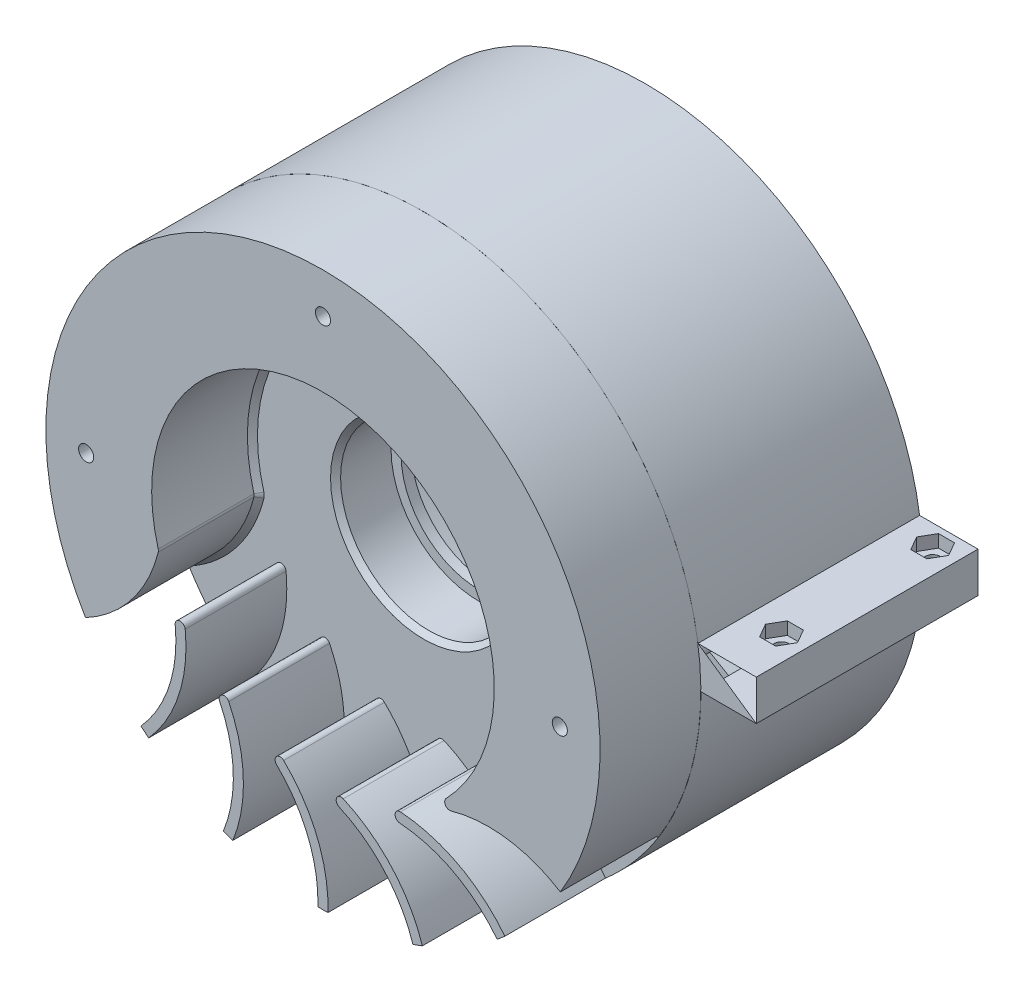
SolidWorks part; units mm, degrees
material "ABS"
ref_plane "前视基准面" through (0, 0, 0) normal (0, 0, 1) x (1, 0, 0)
ref_plane "上视基准面" through (0, 0, 0) normal (0, 1, 0) x (1, 0, 0)
ref_plane "右视基准面" through (0, 0, 0) normal (1, 0, 0) x (0, 0, -1)
other "Configuration Table"
sketch "草图1" plane through (0, 0, 0) normal (1, 0, 0) x (0, 0, -1)
  line L0 (0, 0) -> (32.5576, 0) construction
  line L1 (0, 17.5) -> (44, 17.5)
  line L2 (0, 17.5) -> (0, 55)
  line L3 (0, 55) -> (44, 55)
  line L4 (44, 17.5) -> (44, 55)
  dimension "D1" = 17.5
  dimension "D2" = 55
  dimension "D3" = 44
sketch "草图2" plane through (0, 0, 0) normal (0, 0, 1) x (1, 0, 0)
  line L0 (-33.6531, -9.6161) -> (-22.355, -49.1554) construction
  line L3 (-52.8896, -16.3925) -> (-45.4407, -29.2943) construction
  line L4 (-45.7638, -26.4218) -> (-39.6155, -22.872) construction
  line L5 (0, 0) -> (0, -27.9556) construction
  line L6 (-33.6531, -9.6161) -> (-40.2555, -35.993) construction
  circle A0 centre (0, 0) radius 35 construction
  circle A1 centre (0, 0) radius 54 construction
  arc A4 (-33.6531, -9.6161) -> (-46.7654, -27) centre (-60.7125, -2.8429) cw construction
  arc A5 (-46.2654, -27.866) -> (-32.683, -9.859) centre (-60.7125, -2.8429) ccw
  arc A6 (-47.2654, -26.134) -> (-34.6231, -9.3733) centre (-60.7125, -2.8429) ccw
  arc A7 (-47.2654, -26.134) -> (-46.2654, -27.866) centre (-46.7654, -27) ccw construction
  arc A8 (-32.683, -9.859) -> (-34.6231, -9.3733) centre (-33.6531, -9.6161) ccw
  arc A9 (-47.2654, -26.134) -> (-48.1283, -26.6113) centre (-60.7125, -2.8429) cw
  arc A10 (-54.7677, -5.0001) -> (54.7677, -5.0001) centre (0, 0) ccw construction
  arc A11 (-46.2654, -27.866) -> (-47.1283, -28.3448) centre (-60.7125, -2.8429) cw
  arc A12 (-47.1283, -28.3448) -> (-48.1283, -26.6113) centre (0, 0) cw
  point P6 (-38.4429, -19.6404)
  dimension "D1" = 70
  dimension "D2" = 108
  dimension "D3" = 1
  dimension "D4" = 60
  dimension "D5" = 30
extrude "凸台-拉伸1" add sketch "草图2" along normal blind 20 contours A12 A11 A5 A8 A6 A9
revolve "旋转1" add sketch "草图1" angle 360 about L0
pattern_circular "阵列(圆周)1" count 7 every 20 about axis through (0, 0, 0) along (0, 0, 1) of "凸台-拉伸1"
sketch "草图3" plane through (0, 0, 0) normal (0, 0, 1) x (1, 0, 0)
  arc A9 (-47.1283, -28.3448) -> (47.1103, -28.3747) centre (0, 0) cw
  arc A20 (-32.6916, -9.3414) -> (24.4357, -23.641) centre (0, 0) cw
  arc A22 (24.8796, -23.3748) -> (25.4291, -25.2979) centre (25.1544, -24.3363) ccw construction
  arc A23 (-47.1283, -28.3448) -> (-32.683, -9.859) centre (-60.7125, -2.8429) ccw construction
  arc A24 (-47.1283, -28.3448) -> (-32.683, -9.859) centre (-60.7125, -2.8429) ccw
  arc A25 (47.1103, -28.3747) -> (25.4291, -25.2979) centre (32.8182, -51.1571) ccw
  arc A26 (-32.683, -9.859) -> (-32.6916, -9.3414) centre (-33.6531, -9.6161) ccw
  arc A27 (24.4357, -23.641) -> (25.4291, -25.2979) centre (25.1544, -24.3363) ccw
  arc A28 (47.1103, -28.3747) -> (25.4291, -25.2979) centre (32.8182, -51.1571) ccw construction
extrude "凸台-拉伸2" add sketch "草图3" along normal up to surface (20 mm away) up to face at (-39.6333, -19.0479, 20)
sketch "草图4" plane through (0, 0, -44) normal (0, 0, -1) x (-1, 0, 0)
  line L0 (-50, 0) -> (-47, 0) construction
  line L1 (-45.25, 3.0311) -> (-49.6863, 5.5924)
  line L2 (-45.25, -3.0311) -> (-49.6863, -5.5924)
  line L3 (3.0311, 45.25) -> (5.5924, 49.6863)
  line L4 (-3.0311, 45.25) -> (-5.5924, 49.6863)
  line L5 (0, 50) -> (0, 47) construction
  line L6 (45.25, -3.0311) -> (49.6863, -5.5924)
  line L7 (45.25, 3.0311) -> (49.6863, 5.5924)
  line L8 (50, 0) -> (47, 0) construction
  line L9 (-3.0311, -45.25) -> (-5.5924, -49.6863)
  line L10 (3.0311, -45.25) -> (5.5924, -49.6863)
  line L11 (0, -50) -> (0, -47) construction
  line L12 (-49.9706, -1.7151) -> (-49.9706, 1.7151) construction
  line L13 (-49.9706, 1.7151) -> (-47, 0) construction
  circle A0 centre (0, 0) radius 50 construction
  circle A1 centre (0, 0) radius 55 construction
  arc A2 (-45.25, -3.0311) -> (-45.25, 3.0311) centre (-47, 0) ccw
  circle A3 centre (-47, 0) radius 1.5
  arc A4 (-49.6863, 5.5924) -> (-35.3553, 35.3553) centre (0, 0) cw
  arc A5 (-49.6863, -5.5924) -> (-31.1791, -39.0879) centre (0, 0) ccw
  arc A6 (-3.0311, 45.25) -> (3.0311, 45.25) centre (0, 47) ccw
  circle A7 centre (0, 47) radius 1.5
  arc A8 (5.5924, 49.6863) -> (35.3553, 35.3553) centre (0, 0) cw
  arc A9 (-5.5924, 49.6863) -> (-39.0879, 31.1791) centre (0, 0) ccw
  arc A10 (45.25, 3.0311) -> (45.25, -3.0311) centre (47, 0) ccw
  circle A11 centre (47, 0) radius 1.5
  arc A12 (49.6863, -5.5924) -> (35.3553, -35.3553) centre (0, 0) cw
  arc A13 (49.6863, 5.5924) -> (31.1791, 39.0879) centre (0, 0) ccw
  arc A14 (3.0311, -45.25) -> (-3.0311, -45.25) centre (0, -47) ccw
  circle A15 centre (0, -47) radius 1.5
  arc A16 (-5.5924, -49.6863) -> (-35.3553, -35.3553) centre (0, 0) cw
  arc A17 (5.5924, -49.6863) -> (39.0879, -31.1791) centre (0, 0) ccw
  point P44 (0, 0)
  circle M8 centre (0, 0) radius 17.5
  dimension "D1" = 5
  dimension "D2" = 3
  dimension "D3" = 2
  dimension "D6" = 45
  dimension "D4" = 30
  dimension "D5" = 30
  dimension "D7" = 45
  dimension "D10" = 60
  dimension "D11" = 47
  dimension "D8" = 4
extrude "切除-拉伸1" cut sketch "草图4" against normal offset from surface (33 mm away) 11 contours L10 A17 A12 L6 A10 L7 A13 A8 L3 A6 L4 A9 A4 L1 A2 L2 A5 A16 L9 A14 M8 | A7 | A11 | A15 | A3 up to face at (25.6408, -35.7236, 0)
sketch "草图5" plane through (0, 0, -11) normal (0, 0, -1) x (-1, 0, 0)
  circle A0 centre (-47, 0) radius 1.5 construction
  circle A1 centre (0, 47) radius 1.5
  circle A2 centre (0, 47) radius 1.5
  circle A3 centre (-47, 0) radius 1.5
  circle A6 centre (47, 0) radius 1.5 construction
  circle A7 centre (47, 0) radius 1.5
  dimension "D1" = 0
extrude "切除-拉伸2" cut sketch "草图5" against normal up to surface (31 mm away) up to face at (-0.2385, 1.394, 20)
sketch "草图7" plane through (0, 0, -11) normal (0, 0, -1) x (-1, 0, 0)
  circle A10 centre (0, 0) radius 19.5
  circle A11 centre (0, 0) radius 19.5
  circle A12 centre (0, 0) radius 15.5
  circle A13 centre (0, 0) radius 15.5
  dimension "D1" = 2
  dimension "D2" = 2
extrude "凸台-拉伸3" add sketch "草图7" along normal blind 2
chamfer "倒角2" distance 1 angle 45 1 edges at (17.5, 0, 0)
chamfer "倒角3" distance 1 angle 45 5 edges at (24.2967, -24.8506, 0) (8.2559, 32.9824, 0) (-32.6532, -9.5996, 0) (-37.9451, -20.6339, 0) (36.597, -24.5297, 0)
sketch "草图9" plane through (0, 0, 0) normal (0, 1, 0) x (1, 0, 0)
  line L0 (-55, 44) -> (-55, 0) construction
  line L11 (-55, 44) -> (-55, 0)
  line L12 (-55, 44) -> (-66, 44)
  line L13 (-66, 44) -> (-66, 0)
  line L14 (-66, 0) -> (-55, 0)
  line L15 (0, -55) -> (0, 55) construction
  line L16 (66, 44) -> (66, 0)
  line L17 (55, 44) -> (66, 44)
  line L18 (55, 44) -> (55, 0)
  line L19 (66, 0) -> (55, 0)
  dimension "D1" = 11
extrude "凸台-拉伸4" add sketch "草图9" along normal blind 8
sketch "草图12" plane through (-55, 0, 0) normal (1, 0, 0) x (0, 0, -1)
  line L4 (0, 0) -> (44, 0)
  line L5 (44, 0) -> (44, 8)
  line L6 (44, 8) -> (0, 8)
  line L7 (0, 8) -> (0, 0)
  line L8 (0, 0) -> (44, 0)
  line L9 (44, 0) -> (44, 8)
  line L10 (44, 8) -> (0, 8)
  line L11 (0, 8) -> (0, 0)
  dimension "D1" = 0
extrude "凸台-拉伸6" add sketch "草图12" along normal up to next
sketch "草图14" plane through (0, 0, 0) normal (0, -1, 0) x (1, 0, 0)
  line L0 (-61, -10) -> (-61, -40) construction
  line L1 (0, -55) -> (0, 55) construction
  line L4 (-66, -44) -> (-55, -44)
  line L5 (-55, -44) -> (-55, 0)
  line L6 (-55, 0) -> (-66, 0)
  line L7 (-66, 0) -> (-66, -44)
  line L8 (-66, -44) -> (-55, -44) construction
  line L10 (-55, 0) -> (-66, 0) construction
  line L11 (-66, 0) -> (-66, -44) construction
  line L13 (-55, -44) -> (-55, 0)
  circle A0 centre (-61, -10) radius 1.5
  circle A1 centre (-61, -40) radius 1.5
  circle A2 centre (61, -40) radius 1.5
  circle A3 centre (61, -10) radius 1.5
  dimension "D2" = 3
  dimension "D5" = 3
  dimension "D3" = 10
  dimension "D4" = 6
  dimension "D6" = 30
  dimension "D1" = 0
extrude "切除-拉伸3" cut sketch "草图14" against normal up to next (8 mm away) contours A1 | A0 | A3 | A2
sketch "草图15" plane through (55, 0, 0) normal (-1, 0, 0) x (0, 0, 1)
  line L4 (-44, 0) -> (0, 0)
  line L5 (0, 0) -> (0, 8)
  line L6 (0, 8) -> (-44, 8)
  line L7 (-44, 8) -> (-44, 0)
  line L8 (-44, 0) -> (0, 0)
  line L9 (0, 0) -> (0, 8)
  line L10 (0, 8) -> (-44, 8)
  line L11 (-44, 8) -> (-44, 0)
  dimension "D1" = 0
extrude "凸台-拉伸7" add sketch "草图15" along normal up to next
sketch "草图17" plane through (0, 0, 0) normal (0, -1, 0) x (1, 0, 0)
  line L0 (-61, -10) -> (-61, -40) construction
  line L1 (-57.8246, -40) -> (-59.4123, -37.25)
  line L2 (-59.4123, -37.25) -> (-62.5877, -37.25)
  line L3 (-62.5877, -37.25) -> (-64.1754, -40)
  line L4 (-66, -44) -> (-55, -44)
  line L5 (-55, -44) -> (-55, 0)
  line L6 (-55, 0) -> (-66, 0)
  line L7 (-66, 0) -> (-66, -44)
  line L8 (-66, -44) -> (-55, -44) construction
  line L9 (-55, -44) -> (-55, 0) construction
  line L10 (-55, 0) -> (-66, 0) construction
  line L11 (-66, 0) -> (-66, -44) construction
  line L12 (-64.1754, -40) -> (-62.5877, -42.75)
  line L13 (-62.5877, -42.75) -> (-59.4123, -42.75)
  line L14 (-59.4123, -42.75) -> (-57.8246, -40)
  line L15 (0, -55) -> (0, 55) construction
  line L16 (-59.4123, -7.25) -> (-62.5877, -7.25)
  line L17 (-62.5877, -7.25) -> (-64.1754, -10)
  line L18 (-64.1754, -10) -> (-62.5877, -12.75)
  line L19 (-62.5877, -12.75) -> (-59.4123, -12.75)
  line L20 (-59.4123, -12.75) -> (-57.8246, -10)
  line L21 (-57.8246, -10) -> (-59.4123, -7.25)
  line L22 (59.4123, -42.75) -> (57.8246, -40)
  line L23 (62.5877, -42.75) -> (59.4123, -42.75)
  line L24 (64.1754, -40) -> (62.5877, -42.75)
  line L25 (62.5877, -37.25) -> (64.1754, -40)
  line L26 (59.4123, -37.25) -> (62.5877, -37.25)
  line L27 (57.8246, -40) -> (59.4123, -37.25)
  line L28 (57.8246, -10) -> (59.4123, -7.25)
  line L29 (59.4123, -12.75) -> (57.8246, -10)
  line L30 (62.5877, -12.75) -> (59.4123, -12.75)
  line L31 (64.1754, -10) -> (62.5877, -12.75)
  line L32 (62.5877, -7.25) -> (64.1754, -10)
  line L33 (59.4123, -7.25) -> (62.5877, -7.25)
  circle A0 centre (-61, -40) radius 1.5 construction
  circle A1 centre (-61, -10) radius 1.5 construction
  circle A2 centre (-61, -40) radius 1.5 construction
  circle A3 centre (-61, -10) radius 1.5 construction
  circle A4 centre (-61, -40) radius 2.75 construction
  circle A5 centre (-61, -10) radius 2.75 construction
  dimension "D2" = 5.5
  dimension "D3" = 5.5
  dimension "D1" = 0
extrude "切除-拉伸4" cut sketch "草图17" along normal blind 2.5 from surface at -8 starting at face at (-61, 8, -41.5)
